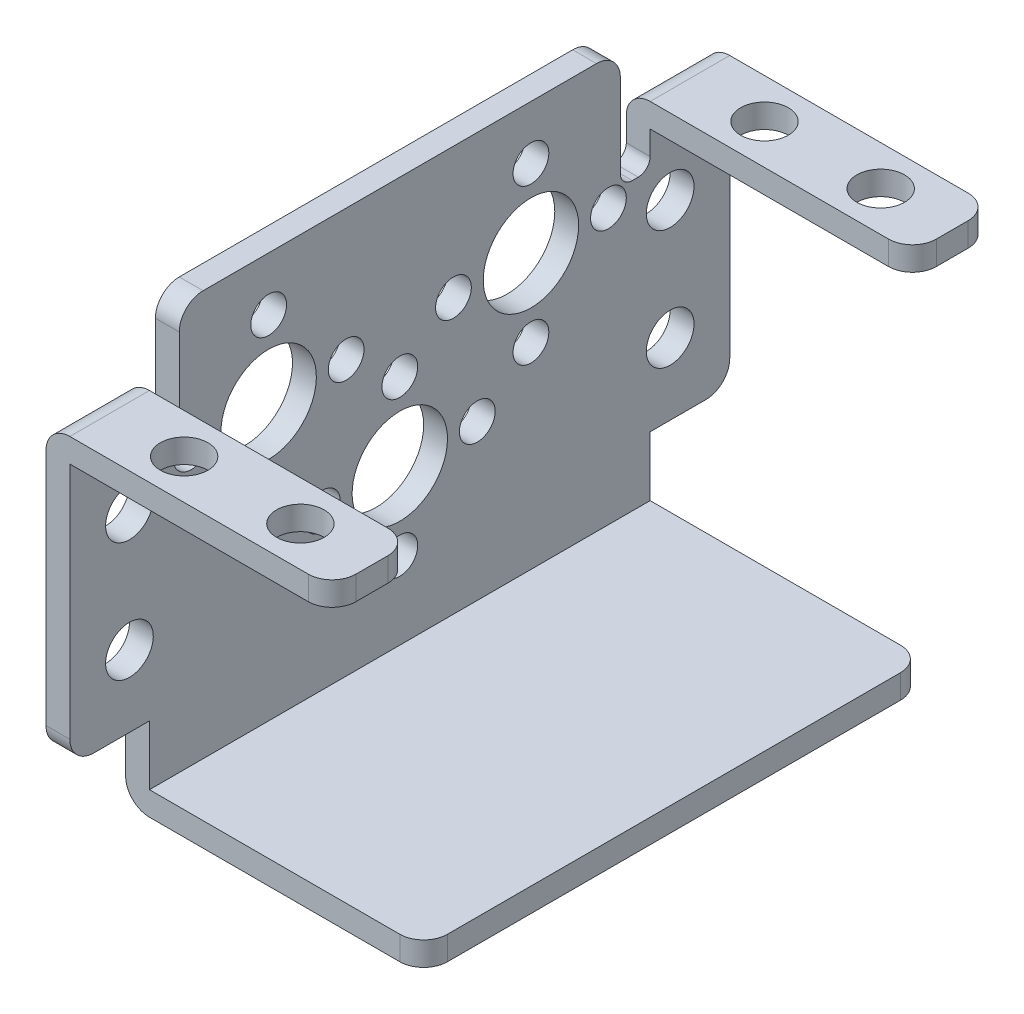
SolidWorks part; units mm, degrees
ref_plane "Front Plane" through (0, 0, 0) normal (0, 0, 1) x (1, 0, 0)
ref_plane "Top Plane" through (0, 0, 0) normal (0, 1, 0) x (1, 0, 0)
ref_plane "Right Plane" through (0, 0, 0) normal (1, 0, 0) x (0, 0, -1)
sketch "Sketch2" plane through (0, 0, 0) normal (0, 1, 0) x (1, 0, 0)
  line L1 (25, -21) -> (0, -21)
  line L2 (25, -21) -> (25, 21)
  line L3 (25, 21) -> (0, 21)
  line L4 (0, -21) -> (0, 21)
  point P4 (0, 0)
  dimension "D1" = 25
  dimension "D2" = 42
extrude "Boss-Extrude1" add sketch "Sketch2" along normal blind 36
sketch "Sketch4" plane through (0, 0, 21) normal (0, 0, 1) x (1, 0, 0)
  line L0 (0, 36) -> (25, 36) construction
  line L1 (2, 36) -> (25, 36)
  line L2 (2, 36) -> (2, 2)
  line L3 (2, 2) -> (25, 2)
  line L4 (25, 36) -> (25, 2)
  line L5 (25, 36) -> (25, 0) construction
  line L6 (0, 0) -> (25, 0) construction
  line L7 (0, 36) -> (0, 0) construction
  dimension "D1" = 2
  dimension "2" = 2
extrude "Cut-Extrude2" cut sketch "Sketch4" against normal through all contours L2 L3 L4 L1
fillet "Fillet2" radius 2 2 edges at (25, 1, -21) (25, 1, 21)
sketch "Sketch5" plane through (2, 0, 0) normal (1, 0, 0) x (0, 0, -1)
  line L1 (-21, 36) -> (-18.5, 36)
  line L2 (-21, 36) -> (-21, 26)
  line L3 (-21, 26) -> (-18.5, 26)
  line L4 (-18.5, 36) -> (-18.5, 26)
  line L5 (21, 36) -> (18.5, 36)
  line L6 (21, 36) -> (21, 26)
  line L7 (21, 26) -> (18.5, 26)
  line L8 (18.5, 36) -> (18.5, 26)
  dimension "D1" = 10
  dimension "D2" = 10
  dimension "D3" = 2.5
  dimension "D4" = 2.5
extrude "Cut-Extrude3" cut sketch "Sketch5" against normal blind 36
fillet "Fillet3" radius 1 2 edges at (1, 26, -18.5) (1, 26, 18.5)
fillet "Fillet4" radius 2 2 edges at (1, 36, 18.5) (1, 36, -18.5)
sketch "Sketch7" plane through (2, 0, 0) normal (1, 0, 0) x (0, 0, -1)
  line L0 (-21, 26) -> (-21, 2) construction
  line L1 (-21, 7) -> (-27.6784, 7)
  line L2 (-21, 7) -> (-21, 31)
  line L3 (-21, 31) -> (-27.6784, 31)
  line L4 (-27.6784, 7) -> (-27.6784, 31)
  line L5 (-21, 26) -> (-19.5, 26) construction
  line L6 (0, 36) -> (0, 0) construction
  line L7 (16.5, 36) -> (-16.5, 36) construction
  line L8 (21, 31) -> (27.6784, 31)
  line L9 (27.6784, 7) -> (27.6784, 31)
  line L10 (21, 7) -> (27.6784, 7)
  line L11 (21, 7) -> (21, 31)
  dimension "D1" = 5
  dimension "D2" = 24
extrude "Boss-Extrude2" add sketch "Sketch7" against normal blind 2
fillet "Fillet5" radius 2 2 edges at (1, 7, 27.6784) (1, 7, -27.6784)
sketch "Sketch8" plane through (2, 0, 0) normal (1, 0, 0) x (0, 0, -1)
  line L0 (-21, 26) -> (-21, 31) construction
  line L1 (-27.6784, 31) -> (-21, 31)
  line L2 (-27.6784, 31) -> (-27.6784, 29)
  line L3 (-27.6784, 29) -> (-21, 29)
  line L4 (-21, 31) -> (-21, 29)
  line L5 (27.6784, 9) -> (27.6784, 31) construction
  line L6 (21, 31) -> (27.6784, 31)
  line L7 (21, 31) -> (21, 29)
  line L8 (21, 29) -> (27.6784, 29)
  line L9 (27.6784, 31) -> (27.6784, 29)
  dimension "D1" = 2
  dimension "D2" = 2
extrude "Boss-Extrude5" add sketch "Sketch8" along normal blind 22
fillet "Fillet6" radius 2 4 edges at (24, 30, -27.6784) (24, 30, -21) (24, 30, 27.6784) (24, 30, 21)
fillet "Fillet7" radius 2 2 edges at (0, 31, -24.3392) (0, 31, 24.3392)
fillet "Fillet8" radius 2 1 edges at (0, 0, 0)
fillet "Fillet9" radius 1 2 edges at (1, 26, 21) (1, 26, -21)
sketch "Sketch10" plane through (2, 0, 0) normal (1, 0, 0) x (0, 0, -1)
  line L0 (-27.6784, 29) -> (-27.6784, 9) construction
  line L1 (-25.6784, 7) -> (-21, 7) construction
  line L2 (0, 36) -> (0, 0) construction
  line L3 (16.5, 36) -> (-16.5, 36) construction
  line L4 (-18.5, 27) -> (-18.5, 34) construction
  circle A0 centre (-22.6784, 13) radius 2
  circle A1 centre (-22.6784, 23) radius 2
  circle A2 centre (22.6784, 13) radius 2
  circle A3 centre (22.6784, 23) radius 2
  circle A4 centre (-11, 25) radius 4
  circle A5 centre (-11, 31.5) radius 1.5
  circle A6 centre (-11, 18.5) radius 1.5
  circle A7 centre (-17.5, 25) radius 1.5
  circle A8 centre (-4.5, 25) radius 1.5
  circle A9 centre (11, 18.5) radius 1.5
  circle A10 centre (4.5, 25) radius 1.5
  circle A11 centre (17.5, 25) radius 1.5
  circle A12 centre (11, 31.5) radius 1.5
  circle A13 centre (11, 25) radius 4
  circle A14 centre (0, 15) radius 4
  circle A15 centre (6.5, 15) radius 1.5
  circle A16 centre (0, 8.5) radius 1.5
  circle A17 centre (0, 21.5) radius 1.5
  circle A18 centre (-6.5, 15) radius 1.5
  dimension "D1" = 4
  dimension "D4" = 4
  dimension "D7" = 8
  dimension "D8" = 3
  dimension "D10" = 3
  dimension "D12" = 3
  dimension "D16" = 3
  dimension "D17" = 8
  dimension "D19" = 3
  dimension "D21" = 3
  dimension "D23" = 3
  dimension "D2" = 5
  dimension "D3" = 6
  dimension "D5" = 10
  dimension "D6" = 7.5
  dimension "D9" = 6.5
  dimension "D11" = 6.5
  dimension "D13" = 6.5
  dimension "D14" = 4.5
  dimension "D15" = 6.5
  dimension "D18" = 10
  dimension "D20" = 6.5
  dimension "D22" = 6.5
  dimension "D24" = 6.5
extrude "Cut-Extrude5" cut sketch "Sketch10" against normal blind 22
sketch "Sketch11" plane through (0, 31, 0) normal (0, 1, 0) x (1, 0, 0)
  line L0 (24, -23) -> (24, -25.6784) construction
  line L1 (0, 0) -> (25, 0) construction
  line L2 (25, 19) -> (25, -19) construction
  circle A0 centre (18, -24.3392) radius 2
  circle A1 centre (8.25, -24.3392) radius 2
  circle A2 centre (18, 24.3392) radius 2
  circle A3 centre (8.25, 24.3392) radius 2
  dimension "D1" = 4
  dimension "D4" = 4
  dimension "D2" = 6
  dimension "D3" = 9.75
extrude "Cut-Extrude6" cut sketch "Sketch11" against normal blind 22
sketch "Sketch14" plane through (0, 0, 0) normal (0, -1, 0) x (1, 0, 0)
  line L0 (25, 0) -> (11.3032, 0) construction
  line L1 (25, 19) -> (25, -19) construction
  circle A0 centre (13.12, 8.82) radius 1.4807
  circle A1 centre (19.62, 9.2153) radius 1.5
  circle A2 centre (6.62, 9.2153) radius 1.5
  circle A3 centre (12.8007, 15.3122) radius 1.5
  circle A4 centre (12.9173, 2.32) radius 1.5
  circle A5 centre (12.9173, -2.32) radius 1.5
  circle A6 centre (19.62, -9.2153) radius 1.5
  circle A7 centre (13.12, -8.82) radius 1.4807
  circle A8 centre (6.62, -9.2153) radius 1.5
  circle A9 centre (12.8007, -15.3122) radius 1.5
  dimension "D1" = 3
  dimension "D2" = 8.82
  dimension "D3" = 11.88
  dimension "D4" = 3
  dimension "D5" = 3
  dimension "D6" = 3
  dimension "D7" = 6.5
  dimension "D8" = 6.5
  dimension "D9" = 6.5
  dimension "D10" = 6.5
extrude "Cut-Extrude8" cut sketch "Sketch14" against normal blind 1
